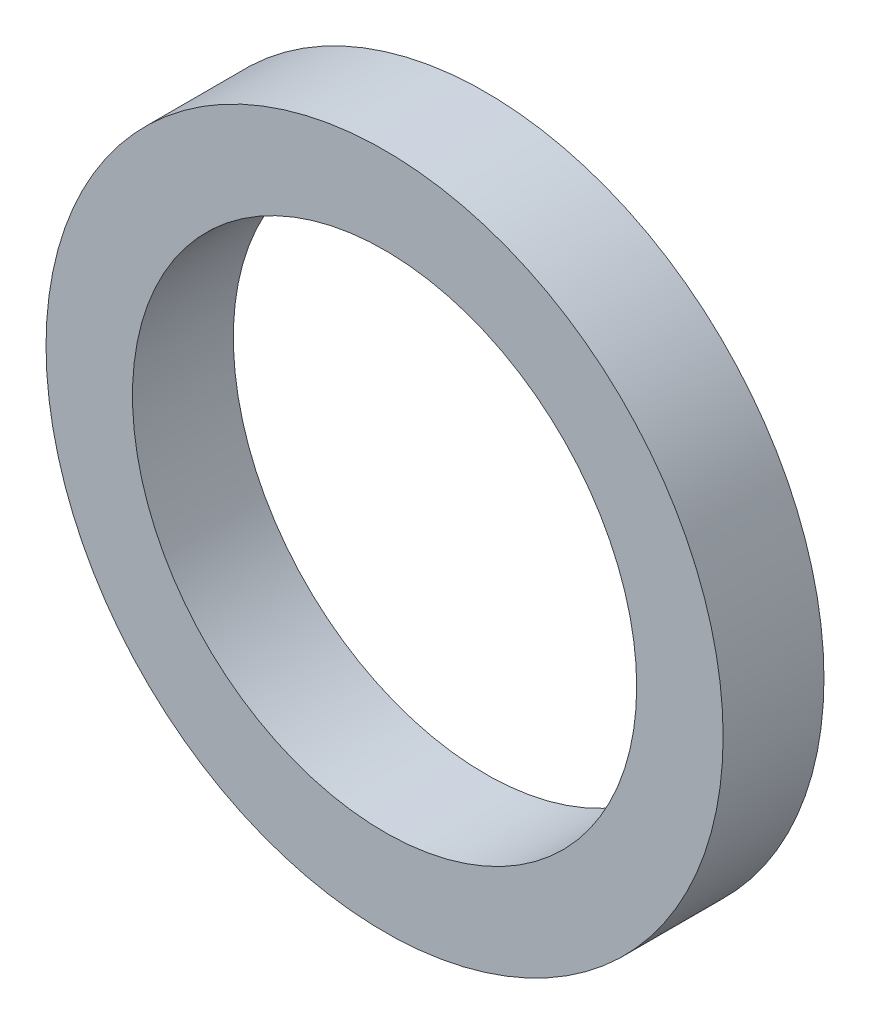
SolidWorks part; units mm, degrees
ref_plane "前视基准面" through (0, 0, 0) normal (0, 0, 1) x (1, 0, 0)
ref_plane "上视基准面" through (0, 0, 0) normal (0, 1, 0) x (1, 0, 0)
ref_plane "右视基准面" through (0, 0, 0) normal (1, 0, 0) x (0, 0, -1)
sketch "草图1" plane through (0, 0, 0) normal (0, 0, 1) x (1, 0, 0)
  circle A0 centre (0, 0) radius 23.5
  circle A1 centre (0, 0) radius 17.5
  dimension "D1" = 47
  dimension "D2" = 35
extrude "凸台-拉伸1" add sketch "草图1" along normal blind 7
